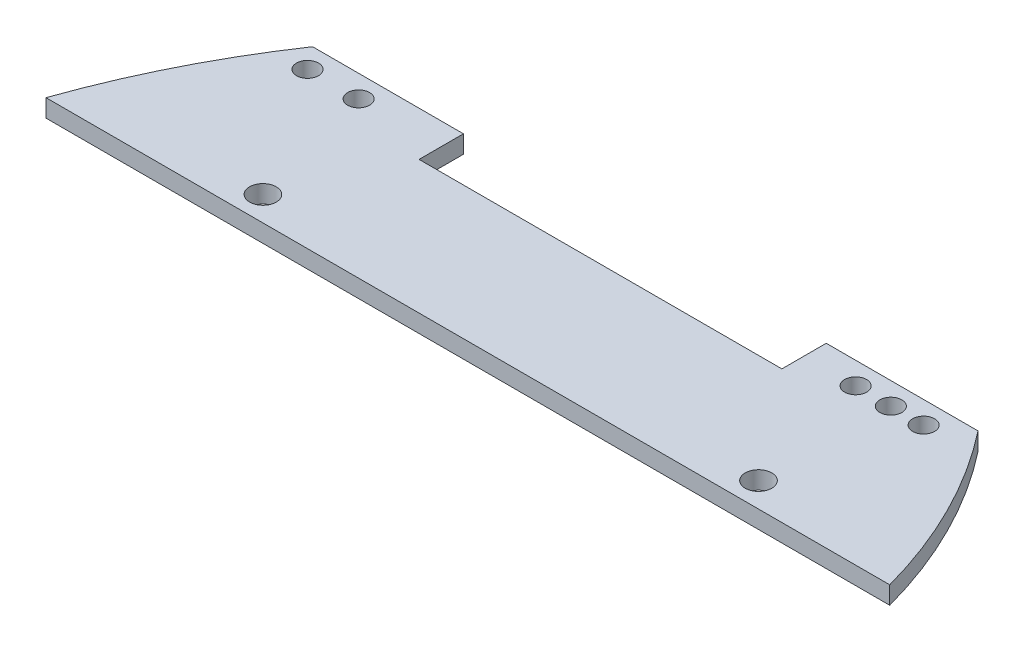
SolidWorks part; units mm, degrees
ref_plane "Front Plane" through (0, 0, 0) normal (0, 0, 1) x (1, 0, 0)
ref_plane "Top Plane" through (0, 0, 0) normal (0, 1, 0) x (1, 0, 0)
ref_plane "Right Plane" through (0, 0, 0) normal (1, 0, 0) x (0, 0, -1)
sketch "Sketch1" plane through (0, 0, 0) normal (0, 1, 0) x (1, 0, 0)
  line L0 (-37.5, 0) -> (37.5, 0)
  line L2 (-47.5513, -20) -> (47.5513, -20)
  arc A0 (-37.5, 0) -> (-47.5513, -20) centre (34.4689, -48.6949) ccw
  arc A1 (37.5, 0) -> (47.5513, -20) centre (-6.5272, -34.6523) cw
  point P4 (0, 0)
  point P9 (0, -20)
  dimension "D1" = 75
extrude "Boss-Extrude1" add sketch "Sketch1" along normal blind 2
sketch "Sketch2" plane through (0, 2, 0) normal (0, 1, 0) x (1, 0, 0)
  line L0 (-37.5, 0) -> (-20.5, 0) construction
  line L1 (37.5, 0) -> (-37.5, 0) construction
  line L2 (-20.5, 0) -> (20.3949, 0)
  line L3 (20.3949, 0) -> (20.3949, -5)
  line L4 (20.3949, -5) -> (-20.5, -5)
  line L5 (-20.5, -5) -> (-20.5, 0)
  line L6 (37.5, 0) -> (20.5, 0) construction
  dimension "D1" = 17
extrude "Cut-Extrude1" cut sketch "Sketch2" against normal blind 2
sketch "Sketch3" plane through (0, 2, 0) normal (0, 1, 0) x (1, 0, 0)
  line L0 (-20.5, -2.5) -> (54.5245, -2.5) construction
  line L1 (-20.5, 0) -> (-20.5, -5) construction
  line L2 (54.5245, -2.5) -> (-20.5, -2.5) construction
  line L3 (-20.5, -2.5) -> (-39.1297, -2.5) construction
  arc A0 (-37.5, 0) -> (-47.5513, -20) centre (34.4689, -48.6949) ccw construction
  circle A1 centre (-29.8148, -2.5) radius 1.24
  circle A2 centre (26.2042, -2.5) radius 1.24
  circle A3 centre (-35.5743, -2.5) radius 1.24
  circle A4 centre (30.1746, -2.5) radius 1.24
  circle A5 centre (33.8698, -2.5) radius 1.24
  point P12 (0, 0)
  point P15 (25.9099, -2.5)
  point P18 (21.7871, -2.5)
  point P21 (17.4716, -2.5)
  point P22 (26.0403, -2.5)
  point P23 (22.1092, -2.5)
  point P24 (18.3083, -2.5)
  point P25 (26.3899, -2.5)
  point P26 (22.8008, -2.5)
  point P27 (19.2443, -2.5)
  point P28 (-29.8148, -2.5)
  point P29 (-29.8148, -2.5)
  point P30 (0, 0)
  point P31 (-35.5743, -2.5)
  point P32 (35.5558, -2.5)
  point P33 (31.7235, -2.5)
  point P34 (27.5014, -2.5)
  point P35 (26.2042, -2.5)
  point P36 (30.1746, -2.5)
  point P37 (33.8698, -2.5)
  dimension "D1" = 2.48
extrude "Cut-Extrude2" cut sketch "Sketch3" against normal blind 2
sketch "Sketch4" plane through (0, 2, 0) normal (0, 1, 0) x (1, 0, 0)
  line L0 (-25.8803, -17.2197) -> (29.9799, -17.2197) construction
  circle A0 centre (-25.8803, -17.2197) radius 1.5
  circle A1 centre (29.9799, -17.2197) radius 1.5
  point P3 (2.0498, -17.2197)
  point P5 (29.9799, -17.2541)
  point P6 (-25.884, -17.1876)
  point P7 (-26.9436, -17.4855)
  point P8 (-25.8803, -17.2197)
  dimension "D1" = 3
  dimension "D2" = 3
extrude "Cut-Extrude3" cut sketch "Sketch4" against normal blind 2
